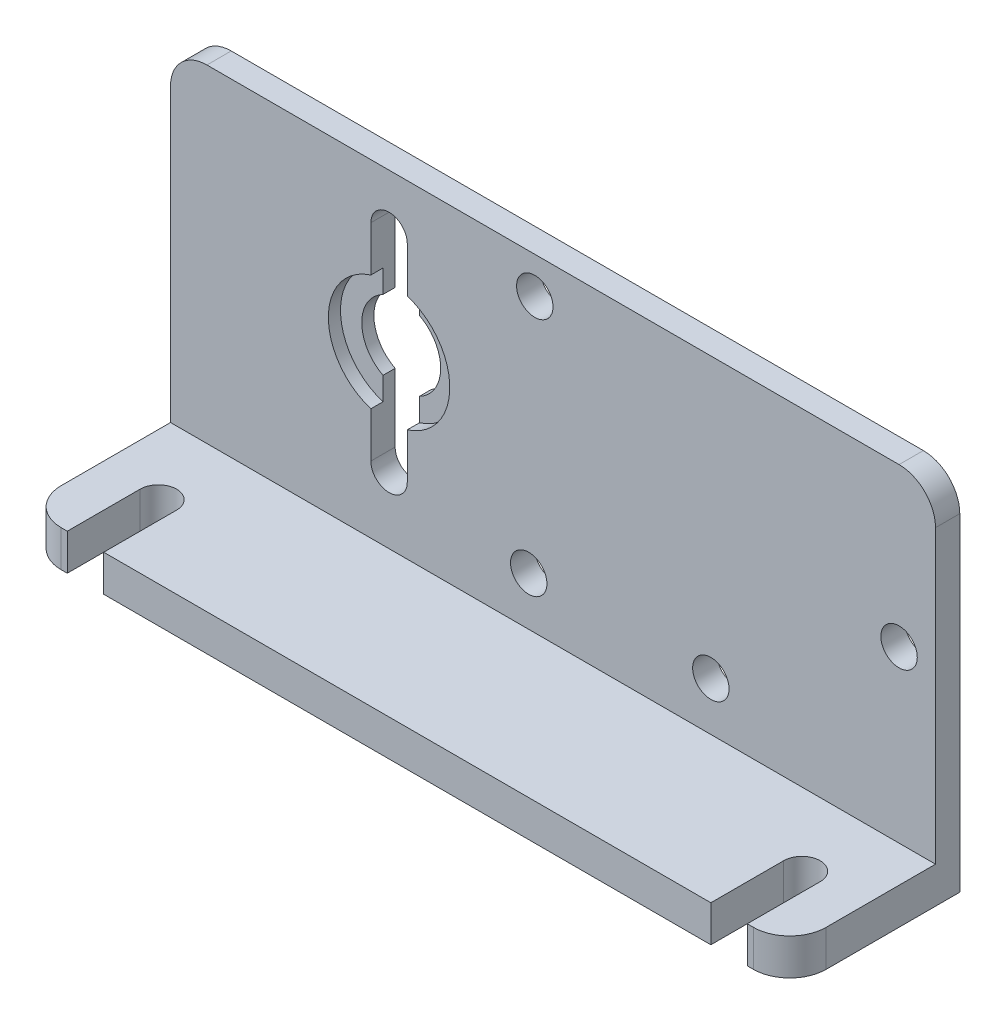
SolidWorks part; units mm, degrees
material "PVC 0.007 Plasticized"
ref_plane "Front Plane" through (0, 0, 0) normal (0, 0, 1) x (1, 0, 0)
ref_plane "Top Plane" through (0, 0, 0) normal (0, 1, 0) x (1, 0, 0)
ref_plane "Right Plane" through (0, 0, 0) normal (1, 0, 0) x (0, 0, -1)
sketch "Sketch1" plane through (0, 0, 0) normal (0, 0, 1) x (1, 0, 0)
  line L1 (31.5, 15) -> (-31.5, 15)
  line L2 (31.5, 15) -> (31.5, -15)
  line L3 (31.5, -15) -> (-31.5, -15)
  line L4 (-31.5, 15) -> (-31.5, -15)
  line L5 (31.5, 15) -> (-31.5, -15) construction
  line L6 (31.5, -15) -> (-31.5, 15) construction
  point P0 (0, 0)
  dimension "D1" = 63
  dimension "D2" = 30
extrude "Boss-Extrude1" add sketch "Sketch1" along normal blind 2
sketch "Sketch2" plane through (0, 0, 2) normal (0, 0, 1) x (1, 0, 0)
  line L0 (31.5, -15) -> (31.5, 15) construction
  line L1 (-31.5, -15) -> (31.5, -15)
  line L2 (-31.5, -15) -> (-31.5, -12)
  line L3 (-31.5, -12) -> (31.5, -12)
  line L4 (31.5, -15) -> (31.5, -12)
  dimension "D1" = 3
extrude "Boss-Extrude2" add sketch "Sketch2" along normal blind 12
sketch "Sketch3" plane through (0, -12, 0) normal (0, 1, 0) x (1, 0, 0)
  line L0 (26.5, -14) -> (26.5, -8) construction
  line L1 (31.5, -14) -> (-31.5, -14) construction
  line L2 (25, -14) -> (25, -8)
  line L3 (28, -14) -> (28, -8)
  line L4 (0, 0) -> (0, -14) construction
  line L5 (-26.5, -14) -> (-26.5, -8) construction
  line L6 (-25, -14) -> (-25, -8)
  line L7 (-28, -14) -> (-28, -8)
  arc A0 (25, -14) -> (28, -14) centre (26.5, -14) ccw
  arc A1 (28, -8) -> (25, -8) centre (26.5, -8) ccw
  arc A2 (-25, -14) -> (-28, -14) centre (-26.5, -14) cw
  arc A3 (-28, -8) -> (-25, -8) centre (-26.5, -8) cw
  point P4 (26.5, -11)
  point P9 (25, -11)
  point P15 (-26.5, -11)
  dimension "D1" = 7.5
  dimension "D2" = 3
  dimension "D3" = 53
extrude "Cut-Extrude1" cut sketch "Sketch3" against normal through all
fillet "Fillet1" radius 3 4 edges at (-31.5, 15, 1) (31.5, 15, 1) (-31.5, -13.5, 14) (31.5, -13.5, 14)
sketch "Sketch4" plane through (0, 0, 2) normal (0, 0, 1) x (1, 0, 0)
  line L0 (-13.5, 10.5) -> (-13.5, -6.5) construction
  line L1 (-12, 10.5) -> (-12, -6.5)
  line L2 (-15, 10.5) -> (-15, -6.5)
  line L3 (-31.5, 12) -> (-31.5, -12) construction
  line L4 (28.5, 15) -> (-28.5, 15) construction
  arc A0 (-12, 10.5) -> (-15, 10.5) centre (-13.5, 10.5) ccw
  arc A1 (-15, -6.5) -> (-12, -6.5) centre (-13.5, -6.5) ccw
  point P2 (-13.5, 2)
  dimension "D2" = 20
  dimension "D1" = 3
  dimension "D3" = 18
  dimension "D4" = 4.5
extrude "Cut-Extrude2" cut sketch "Sketch4" against normal through all
sketch "Sketch5" plane through (0, 0, 2) normal (0, 0, 1) x (1, 0, 0)
  line L0 (-12, 2) -> (-13.5, 2) construction
  line L1 (-12, -6.5) -> (-12, 10.5) construction
  line L2 (-15, 2) -> (-13.5, 2) construction
  line L3 (-15, 10.5) -> (-15, -6.5) construction
  circle A0 centre (-13.5, 2) radius 5
  dimension "D1" = 10
extrude "Cut-Extrude3" cut sketch "Sketch5" against normal blind 1
sketch "Sketch6" plane through (0, 0, 1) normal (0, 0, 1) x (1, 0, 0)
  circle A0 centre (-13.5, 2) radius 3.25
  dimension "D1" = 6.5
extrude "Cut-Extrude4" cut sketch "Sketch6" against normal through all
sketch "Sketch7" plane through (0, 0, 2) normal (0, 0, 1) x (1, 0, 0)
  line L0 (-13.5, 2) -> (28.5, 2) construction
  line L1 (28.5, 2) -> (31.5, 2) construction
  line L2 (-31.5, 12) -> (-31.5, -12) construction
  line L3 (-31.5, 12) -> (-1.5, 12) construction
  line L4 (28.5, 15) -> (-28.5, 15) construction
  line L5 (31.5, -12) -> (31.5, 12) construction
  line L6 (31.5, -8) -> (13, -8) construction
  line L7 (13, -8) -> (-2, -8) construction
  line L8 (31.5, -12) -> (-31.5, -12) construction
  circle A0 centre (28.5, 2) radius 1.5
  circle A1 centre (-1.5, 12) radius 1.5
  circle A2 centre (-2, -8) radius 1.5
  circle A3 centre (13, -8) radius 1.5
  dimension "D1" = 3
  dimension "D4" = 3
  dimension "D6" = 3
  dimension "D7" = 3
  dimension "D2" = 3
  dimension "D3" = 30
  dimension "D5" = 3
  dimension "D8" = 18.5
  dimension "D9" = 4
  dimension "D10" = 15
extrude "Cut-Extrude5" cut sketch "Sketch7" against normal through all
